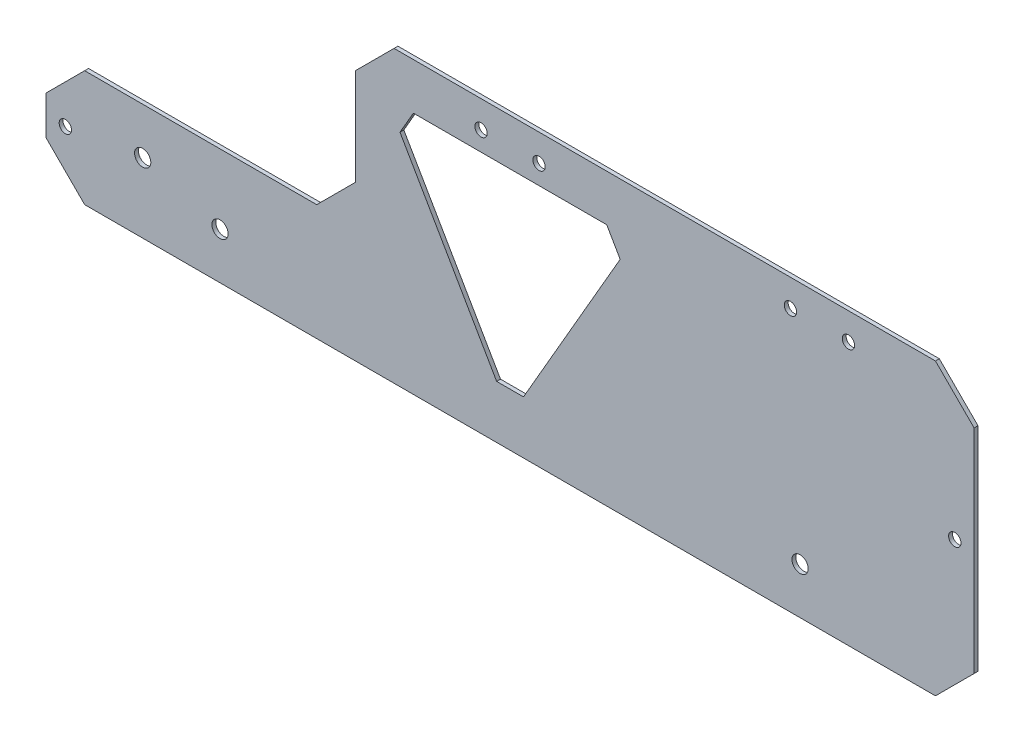
SolidWorks part; units mm, degrees
ref_plane "前视基准面" through (0, 0, 0) normal (0, 0, 1) x (1, 0, 0)
ref_plane "上视基准面" through (0, 0, 0) normal (0, 1, 0) x (1, 0, 0)
ref_plane "右视基准面" through (0, 0, 0) normal (1, 0, 0) x (0, 0, -1)
sketch "草图1" plane through (0, 0, 0) normal (0, 0, 1) x (1, 0, 0)
  line L0 (120, 0) -> (120, -120) construction
  line L1 (0, 0) -> (240, 0)
  line L2 (0, 0) -> (0, 75)
  line L3 (0, 75) -> (240, 75)
  line L4 (240, 0) -> (240, 75)
  line L5 (120, -120) -> (0, 0) construction
  line L6 (120, -120) -> (240, 0) construction
  line L7 (120, 75) -> (120, 0) construction
  dimension "D1" = 240
  dimension "D2" = 75
extrude "凸台-拉伸1" add sketch "草图1" along normal blind 1
sketch "草图3" plane through (0, 0, 0) normal (0, 0, -1) x (-1, 0, 0)
  line L0 (-120, 0) -> (-120, 75) construction
  line L1 (0, 0) -> (-240, 0) construction
  line L2 (-240, 75) -> (0, 75) construction
  line L3 (-135, 33.6603) -> (-148.4697, 56.9904)
  line L4 (-100, 25) -> (-110, 42.3205)
  line L5 (-110, 42.3205) -> (-130, 42.3205)
  line L6 (-130, 42.3205) -> (-140, 25)
  line L7 (-140, 25) -> (-130, 7.6795)
  line L8 (-130, 7.6795) -> (-110, 7.6795)
  line L9 (-110, 7.6795) -> (-100, 25)
  line L10 (-148.4697, 56.9904) -> (-145, 63)
  line L11 (-145, 63) -> (-95, 63)
  line L12 (-240, 75) -> (0, 75) construction
  line L13 (-105, 33.6603) -> (-91.5303, 56.9904)
  line L14 (-91.5303, 56.9904) -> (-95, 63)
  circle A0 centre (-120, 25) radius 17.3205 construction
  point P23 (-120, 63)
  dimension "D1" = 20
  dimension "D2" = 25
  dimension "D3" = 12
  dimension "D4" = 25
extrude "切除-拉伸2" cut sketch "草图3" against normal blind 10 contours L8 L9 L4 L5 L6 L7 | L13 L14 L11 L10 L3 L6 L5 L4
sketch "草图4" plane through (0, 0, 0) normal (0, 0, -1) x (-1, 0, 0)
  line L0 (-80, 75) -> (-80, 30)
  line L1 (-240, 75) -> (0, 75) construction
  line L2 (-80, 30) -> (0, 30)
  line L3 (0, 75) -> (0, 0) construction
  line L4 (0, 30) -> (0, 75)
  line L5 (0, 75) -> (-80, 75)
  dimension "D1" = 80
  dimension "D2" = 45
extrude "切除-拉伸3" cut sketch "草图4" against normal blind 10
chamfer "倒角1" distance 10 angle 45 6 edges at (80, 75, 0.5) (240, 75, 0.5) (0, 0, 0.5) (0, 30, 0.5) (80, 30, 0.5) (240, 0, 0.5)
sketch "草图5" plane through (0, 0, 0) normal (0, 0, -1) x (-1, 0, 0)
  line L0 (0, 15) -> (-5, 15) construction
  line L1 (0, 20) -> (0, 10) construction
  line L2 (-195, 12) -> (-45, 12) construction
  line L3 (-120, 0) -> (-120, 12) construction
  line L4 (-10, 0) -> (-230, 0) construction
  line L5 (-240, 37.5) -> (-235, 37.5) construction
  line L6 (-240, 10) -> (-240, 65) construction
  line L7 (-207.5, 68) -> (-192.5, 68) construction
  line L8 (-160, 75) -> (-160, 45) construction
  line L9 (-230, 75) -> (-90, 75) construction
  line L10 (-200, 68) -> (-200, 75) construction
  line L11 (-120, 68) -> (-120, 75) construction
  line L12 (-112.5, 68) -> (-127.5, 68) construction
  line L13 (-10, 30) -> (-61.8198, 30) construction
  circle A0 centre (-5, 15) radius 1.6
  circle A1 centre (-195, 12) radius 2.1
  circle A2 centre (-45, 12) radius 2.1
  circle A3 centre (-235, 37.5) radius 1.6
  circle A4 centre (-207.5, 68) radius 1.6
  circle A5 centre (-192.5, 68) radius 1.6
  circle A6 centre (-127.5, 68) radius 1.6
  circle A7 centre (-112.5, 68) radius 1.6
  circle A8 centre (-25, 18) radius 2.1
  dimension "D2" = 3.2
  dimension "D4" = 4.2
  dimension "D7" = 3.2
  dimension "D10" = 3.2
  dimension "D1" = 5
  dimension "D3" = 150
  dimension "D5" = 12
  dimension "D6" = 5
  dimension "D8" = 30
  dimension "D9" = 15
  dimension "D11" = 7
  dimension "D12" = 40
  dimension "D13" = 12
  dimension "D14" = 20
extrude "切除-拉伸4" cut sketch "草图5" against normal blind 10
sketch "草图6" plane through (0, 0, 0) normal (0, 0, -1) x (-1, 0, 0)
  line L0 (-135, 33.6603) -> (-123.4697, 13.6891)
  line L1 (-123.4697, 13.6891) -> (-116.5303, 13.6891)
  line L2 (-116.5303, 13.6891) -> (-105, 33.6603)
  line L4 (-105, 33.6603) -> (-91.5303, 56.9904) construction
  line L5 (-135, 33.6603) -> (-148.4697, 56.9904) construction
  line L6 (-135, 33.6603) -> (-140, 25)
  line L7 (-140, 25) -> (-130, 7.6795)
  line L8 (-130, 7.6795) -> (-110, 7.6795)
  line L9 (-110, 7.6795) -> (-100, 25)
  line L10 (-100, 25) -> (-105, 33.6603)
  dimension "D1" = 50
extrude "凸台-拉伸2" add sketch "草图6" against normal blind 1
